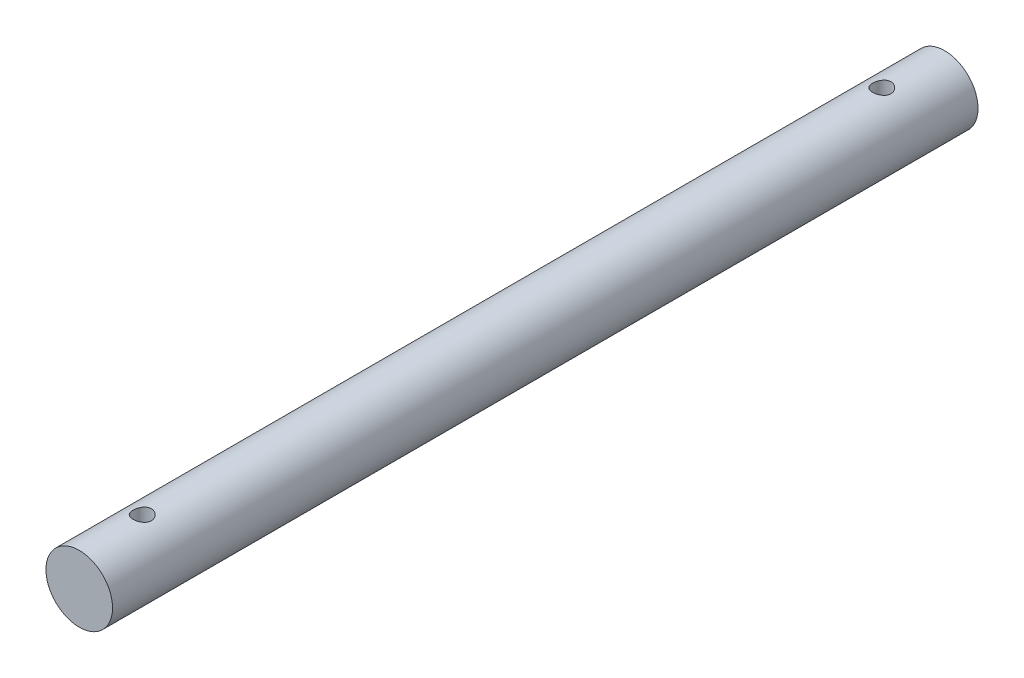
SolidWorks part; units mm, degrees
ref_plane "Alzado" through (0, 0, 0) normal (0, 0, 1) x (1, 0, 0)
ref_plane "Planta" through (0, 0, 0) normal (0, 1, 0) x (1, 0, 0)
ref_plane "Vista lateral" through (0, 0, 0) normal (1, 0, 0) x (0, 0, -1)
sketch "Croquis1" plane through (0, 0, 0) normal (0, 0, 1) x (1, 0, 0)
  circle A0 centre (0, 0) radius 6.35
  dimension "D1" = 12.7
extrude "Saliente-Extruir1" add sketch "Croquis1" along normal blind 165
sketch "Croquis2" plane through (0, 0, 0) normal (0, 1, 0) x (1, 0, 0)
  line L0 (0, 0) -> (0, -165) construction
  line L1 (-6.35, -165) -> (6.35, -165) construction
  line L2 (0, -82.5) -> (-6.35, -82.5) construction
  line L3 (-6.35, 0) -> (-6.35, -165) construction
  circle A0 centre (0, -12) radius 1.75
  circle A1 centre (0, -153) radius 1.75
  dimension "D1" = 3.5
  dimension "D2" = 12
extrude "Cortar-Extruir1" cut sketch "Croquis2" against normal through all both and the other way through all
